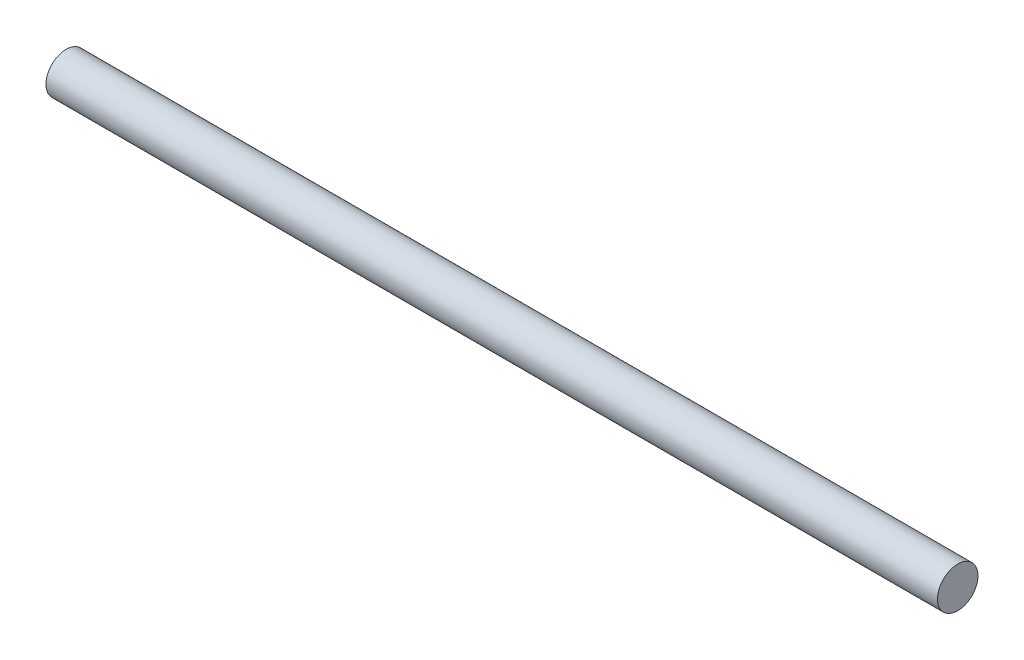
SolidWorks part; units mm, degrees
material "Alloy Steel"
ref_plane "Front Plane" through (0, 0, 0) normal (0, 0, 1) x (1, 0, 0)
ref_plane "Top Plane" through (0, 0, 0) normal (0, 1, 0) x (1, 0, 0)
ref_plane "Right Plane" through (0, 0, 0) normal (1, 0, 0) x (0, 0, -1)
sketch "Sketch1" plane through (0, 0, 0) normal (1, 0, 0) x (0, 0, -1)
  circle A0 centre (0, 0) radius 3.175
  dimension "D1" = 6.35
extrude "Boss-Extrude1" add sketch "Sketch1" along normal mid plane 139.7
